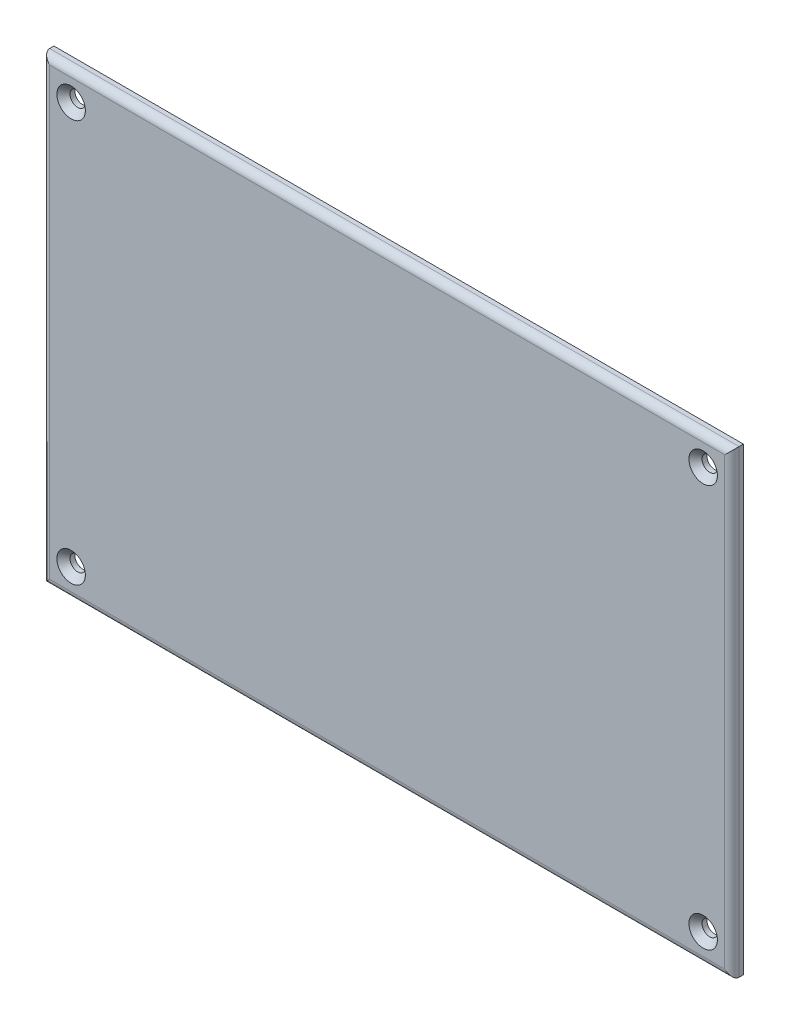
SolidWorks part; units mm, degrees
material "PET"
ref_plane "Front Plane" through (0, 0, 0) normal (0, 0, 1) x (1, 0, 0)
ref_plane "Top Plane" through (0, 0, 0) normal (0, 1, 0) x (1, 0, 0)
ref_plane "Right Plane" through (0, 0, 0) normal (1, 0, 0) x (0, 0, -1)
sketch "Sketch1" plane through (0, 0, 0) normal (0, 0, 1) x (1, 0, 0)
  line L1 (0, 0) -> (152.4, 0)
  line L2 (0, 0) -> (0, 101.6)
  line L3 (0, 101.6) -> (152.4, 101.6)
  line L4 (152.4, 0) -> (152.4, 101.6)
  dimension "D1" = 152.4
  dimension "D2" = 101.6
extrude "Boss-Extrude1" add sketch "Sketch1" along normal blind 2.54
fillet "Fillet1" radius 1.5875 4 edges at (76.2, 101.6, 2.54) (152.4, 50.8, 2.54) (76.2, 0, 2.54) (0, 50.8, 2.54)
hole_wizard "CSK for M3 Flat Head Machine Screw1" positions "Sketch3" profile "Sketch4" countersink size "M3" standard "ANSI Metric"
sketch "Sketch3" plane through (0, 0, 2.54) normal (0, 0, 1) x (1, 0, 0)
  line L0 (6.35, 6.35) -> (6.35, 95.25) construction
  line L1 (6.35, 95.25) -> (146.05, 95.25) construction
  line L3 (76.2, 95.25) -> (76.2, 101.6) construction
  line L4 (0, 101.6) -> (152.4, 101.6) construction
  line L6 (6.35, 50.8) -> (0, 50.8) construction
  line L7 (0, 0) -> (0, 101.6) construction
  point P0 (6.35, 95.25)
  point P2 (6.35, 6.35)
  point P4 (146.05, 6.35)
  point P6 (146.05, 95.25)
  dimension "D1" = 139.7
  dimension "D2" = 88.9
sketch "Sketch4" plane through (6.35, 95.25, 2.54) normal (1, 0, 0) x (0, -1, 0)
  line L0 (0, 0) -> (0, 7.3715)
  line L1 (0, 7.3715) -> (1.7, 6.35)
  line L2 (1.7, 6.35) -> (1.7, 1.45)
  line L3 (1.7, 1.45) -> (3.15, 0)
  line L5 (3.15, 0) -> (0, 0)
  line L6 (-1.7, 1.45) -> (-3.15, 0) construction
  line L10 (0, 7.3715) -> (-1.7, 6.35) construction
  line L11 (0, -6.35) -> (0, 107.95) construction
  dimension "Hole Dia." = 3.4
  dimension "Hole Depth" = 6.35
  dimension "Near C'Sink Dia." = 6.3
  dimension "Near C'Sink Angle" = 90
  dimension "Drill Angle" = 118
